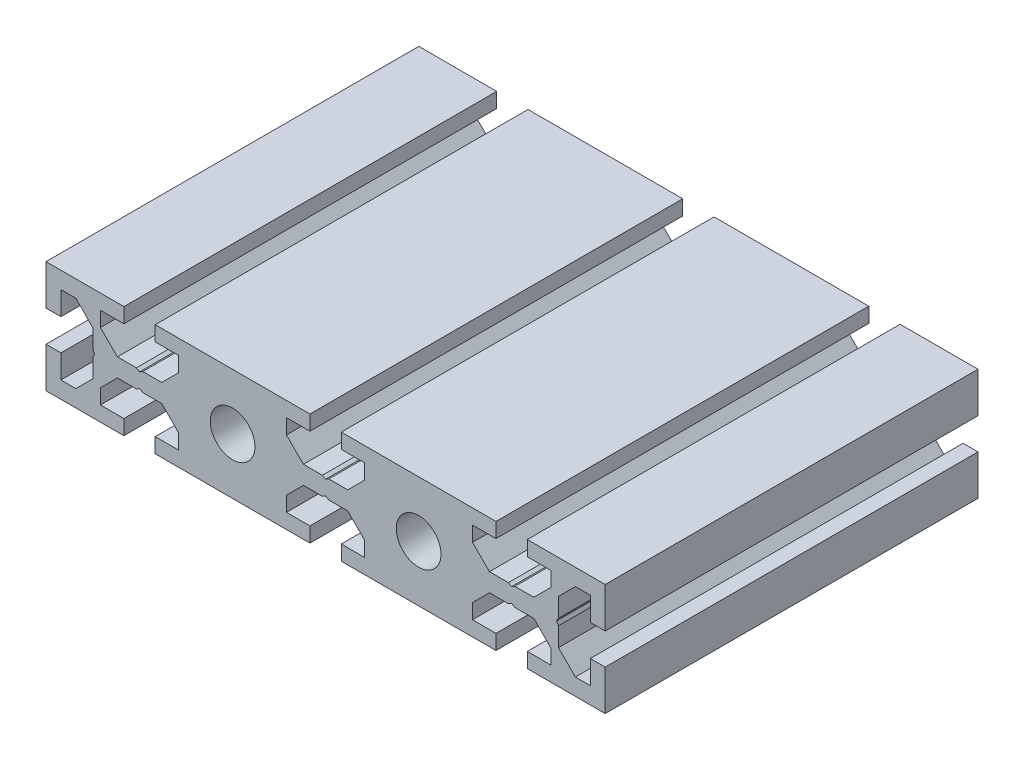
SolidWorks part; units mm, degrees
ref_plane "前视基准面" through (0, 0, 0) normal (0, 0, 1) x (1, 0, 0)
ref_plane "上视基准面" through (0, 0, 0) normal (0, 1, 0) x (1, 0, 0)
ref_plane "右视基准面" through (0, 0, 0) normal (1, 0, 0) x (0, 0, -1)
sketch "草图1" plane through (0, 0, 0) normal (0, 0, 1) x (1, 0, 0)
  line B0 (99.95, 4.2) -> (99.95, 15)
  line B1 (99.95, 15) -> (79.05, 15)
  line B2 (79.05, 15) -> (79.05, 11)
  line B3 (79.05, 11) -> (85.35, 11)
  line B4 (85.35, 11) -> (85.35, 7)
  line B5 (85.35, 7) -> (80.8, 2.45)
  line B6 (80.8, 2.45) -> (75.716, 2.45)
  line B7 (75.716, 2.45) -> (74.85, 1.95)
  line B8 (74.85, 1.95) -> (73.984, 2.45)
  line B9 (73.984, 2.45) -> (68.9, 2.45)
  line B10 (68.9, 2.45) -> (64.35, 7)
  line B11 (64.35, 7) -> (64.35, 11)
  line B12 (64.35, 11) -> (70.65, 11)
  line B13 (70.65, 11) -> (70.65, 15)
  line B14 (70.65, 15) -> (29.15, 15)
  line B15 (29.15, 15) -> (29.15, 11)
  line B16 (29.15, 11) -> (35.45, 11)
  line B17 (35.45, 11) -> (35.45, 7)
  line B18 (35.45, 7) -> (30.9, 2.45)
  line B19 (30.9, 2.45) -> (25.816, 2.45)
  line B20 (25.816, 2.45) -> (24.95, 1.95)
  line B21 (24.95, 1.95) -> (24.084, 2.45)
  line B22 (24.084, 2.45) -> (19, 2.45)
  line B23 (19, 2.45) -> (14.45, 7)
  line B24 (14.45, 7) -> (14.45, 11)
  line B25 (14.45, 11) -> (20.75, 11)
  line B26 (20.75, 11) -> (20.75, 15)
  line B27 (20.75, 15) -> (-20.75, 15)
  line B28 (-20.75, 15) -> (-20.75, 11)
  line B29 (-20.75, 11) -> (-14.45, 11)
  line B30 (-14.45, 11) -> (-14.45, 7)
  line B31 (-14.45, 7) -> (-19, 2.45)
  line B32 (-19, 2.45) -> (-24.084, 2.45)
  line B33 (-24.084, 2.45) -> (-24.95, 1.95)
  line B34 (-24.95, 1.95) -> (-25.816, 2.45)
  line B35 (-25.816, 2.45) -> (-30.9, 2.45)
  line B36 (-30.9, 2.45) -> (-35.45, 7)
  line B37 (-35.45, 7) -> (-35.45, 11)
  line B38 (-35.45, 11) -> (-29.15, 11)
  line B39 (-29.15, 11) -> (-29.15, 15)
  line B40 (-29.15, 15) -> (-50.05, 15)
  line B41 (-50.05, 15) -> (-50.05, 4.2)
  line B42 (-50.05, 4.2) -> (-46.05, 4.2)
  line B43 (-46.05, 4.2) -> (-46.05, 10.5)
  line B44 (-46.05, 10.5) -> (-42.05, 10.5)
  line B45 (-42.05, 10.5) -> (-37.5, 5.95)
  line B46 (-37.5, 5.95) -> (-37.5, 0.866)
  line B47 (-37.5, 0.866) -> (-37, 0)
  line B48 (-37, 0) -> (-37.5, -0.866)
  line B49 (-37.5, -0.866) -> (-37.5, -5.95)
  line B50 (-37.5, -5.95) -> (-42.05, -10.5)
  line B51 (-42.05, -10.5) -> (-46.05, -10.5)
  line B52 (-46.05, -10.5) -> (-46.05, -4.2)
  line B53 (-46.05, -4.2) -> (-50.05, -4.2)
  line B54 (-50.05, -4.2) -> (-50.05, -15)
  line B55 (-50.05, -15) -> (-29.15, -15)
  line B56 (-29.15, -15) -> (-29.15, -11)
  line B57 (-29.15, -11) -> (-35.45, -11)
  line B58 (-35.45, -11) -> (-35.45, -7)
  line B59 (-35.45, -7) -> (-30.9, -2.45)
  line B60 (-30.9, -2.45) -> (-25.816, -2.45)
  line B61 (-25.816, -2.45) -> (-24.95, -1.95)
  line B62 (-24.95, -1.95) -> (-24.084, -2.45)
  line B63 (-24.084, -2.45) -> (-19, -2.45)
  line B64 (-19, -2.45) -> (-14.45, -7)
  line B65 (-14.45, -7) -> (-14.45, -11)
  line B66 (-14.45, -11) -> (-20.75, -11)
  line B67 (-20.75, -11) -> (-20.75, -15)
  line B68 (-20.75, -15) -> (20.75, -15)
  line B69 (20.75, -15) -> (20.75, -11)
  line B70 (20.75, -11) -> (14.45, -11)
  line B71 (14.45, -11) -> (14.45, -7)
  line B72 (14.45, -7) -> (19, -2.45)
  line B73 (19, -2.45) -> (24.084, -2.45)
  line B74 (24.084, -2.45) -> (24.95, -1.95)
  line B75 (24.95, -1.95) -> (25.816, -2.45)
  line B76 (25.816, -2.45) -> (30.9, -2.45)
  line B77 (30.9, -2.45) -> (35.45, -7)
  line B78 (35.45, -7) -> (35.45, -11)
  line B79 (35.45, -11) -> (29.15, -11)
  line B80 (29.15, -11) -> (29.15, -15)
  line B81 (29.15, -15) -> (70.65, -15)
  line B82 (70.65, -15) -> (70.65, -11)
  line B83 (70.65, -11) -> (64.35, -11)
  line B84 (64.35, -11) -> (64.35, -7)
  line B85 (64.35, -7) -> (68.9, -2.45)
  line B86 (68.9, -2.45) -> (73.984, -2.45)
  line B87 (73.984, -2.45) -> (74.85, -1.95)
  line B88 (74.85, -1.95) -> (75.716, -2.45)
  line B89 (75.716, -2.45) -> (80.8, -2.45)
  line B90 (80.8, -2.45) -> (85.35, -7)
  line B91 (85.35, -7) -> (85.35, -11)
  line B92 (85.35, -11) -> (79.05, -11)
  line B93 (79.05, -11) -> (79.05, -15)
  line B94 (79.05, -15) -> (99.95, -15)
  line B95 (99.95, -15) -> (99.95, -4.2)
  line B96 (99.95, -4.2) -> (95.95, -4.2)
  line B97 (95.95, -4.2) -> (95.95, -10.5)
  line B98 (95.95, -10.5) -> (91.95, -10.5)
  line B99 (91.95, -10.5) -> (87.4, -5.95)
  line B100 (87.4, -5.95) -> (87.4, -0.866)
  line B101 (87.4, -0.866) -> (86.9, 0)
  line B102 (86.9, 0) -> (87.4, 0.866)
  line B103 (87.4, 0.866) -> (87.4, 5.95)
  line B104 (87.4, 5.95) -> (91.95, 10.5)
  line B105 (91.95, 10.5) -> (95.95, 10.5)
  line B106 (95.95, 10.5) -> (95.95, 4.2)
  line B107 (95.95, 4.2) -> (99.95, 4.2)
  circle B108 centre (0, 0) radius 6
  circle B109 centre (49.9, 0) radius 6
sketch_block_instance "A$C3F122AB0-1"
sketch_block "A$C3F122AB0"
extrude "凸台-拉伸1" add sketch "草图1" along normal blind 100
